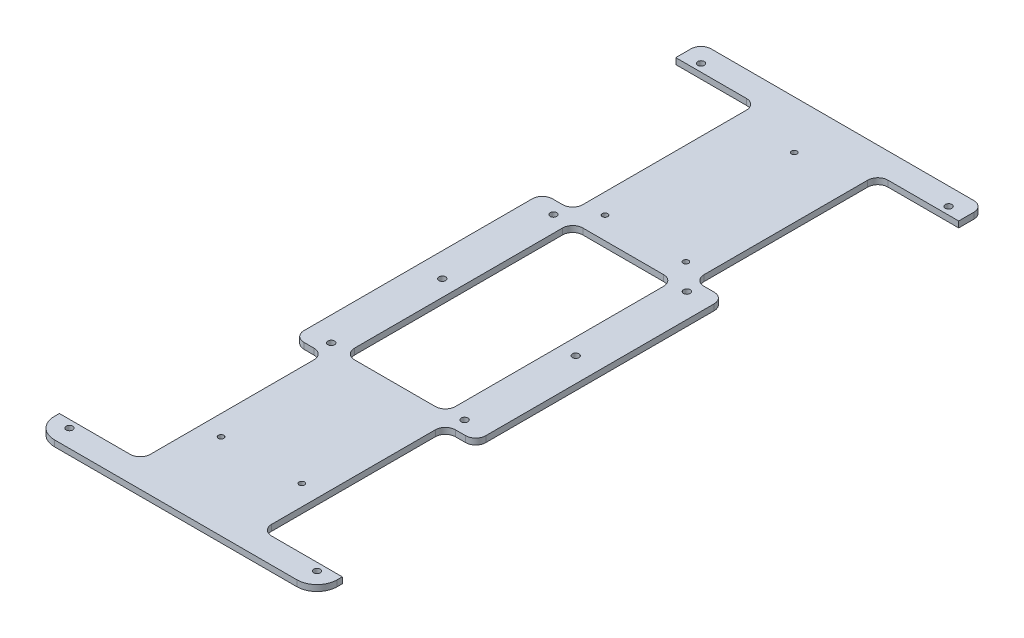
SolidWorks part; units mm, degrees
ref_plane "Front Plane" through (0, 0, 0) normal (0, 0, 1) x (1, 0, 0)
ref_plane "Top Plane" through (0, 0, 0) normal (0, 1, 0) x (1, 0, 0)
ref_plane "Right Plane" through (0, 0, 0) normal (1, 0, 0) x (0, 0, -1)
sketch "Sketch1" plane through (0, 0, 0) normal (0, 1, 0) x (1, 0, 0)
  line L0 (0, 0) -> (140, 0)
  line L1 (0, 0) -> (140, 0) construction
  line L2 (0, 0) -> (0, 330) construction
  line L3 (0, 330) -> (140, 330) construction
  line L4 (140, 0) -> (140, 330) construction
  line L5 (140, 0) -> (140, 12.5)
  line L6 (140, 12.5) -> (100, 12.5)
  line L7 (100, 12.5) -> (100, 103.5)
  line L11 (100, 226.5) -> (100, 317.5)
  line L12 (100, 317.5) -> (140, 317.5)
  line L13 (140, 317.5) -> (140, 330)
  line L14 (140, 330) -> (0, 330)
  line L15 (0, 330) -> (0, 317.5)
  line L16 (0, 317.5) -> (40, 317.5)
  line L17 (40, 317.5) -> (40, 226.5)
  line L21 (40, 103.5) -> (40, 12.5)
  line L22 (40, 12.5) -> (0, 12.5)
  line L23 (0, 12.5) -> (0, 0)
  line L24 (40, 226.5) -> (25, 226.5)
  line L25 (25, 226.5) -> (25, 103.5)
  line L26 (25, 103.5) -> (40, 103.5)
  line L27 (100, 226.5) -> (115, 226.5)
  line L28 (115, 226.5) -> (115, 103.5)
  line L29 (115, 103.5) -> (100, 103.5)
  dimension "D1" = 140
  dimension "D2" = 330
  dimension "D3" = 40
  dimension "D4" = 91
  dimension "D5" = 25
  dimension "D6" = 123
extrude "Boss-Extrude1" add sketch "Sketch1" along normal blind 3
fillet "Fillet1" radius 10 2 edges at (140, 1.5, 0) (0, 1.5, 0)
fillet "Fillet2" radius 5 6 edges at (0, 1.5, -330) (140, 1.5, -330) (115, 1.5, -226.5) (115, 1.5, -103.5) (25, 1.5, -103.5) (25, 1.5, -226.5)
sketch "Sketch2" plane through (0, 3, 0) normal (0, 1, 0) x (1, 0, 0)
  line L2 (37, 220) -> (37, 110) construction
  line L3 (25, 165) -> (37, 165) construction
  line L4 (25, 221.5) -> (25, 108.5) construction
  line L5 (70, 330) -> (70, 0) construction
  line L6 (135, 330) -> (5, 330) construction
  line L7 (10, 0) -> (130, 0) construction
  circle A0 centre (37, 220) radius 1.65
  circle A1 centre (37, 165) radius 1.65
  circle A2 centre (37, 110) radius 1.65
  circle A3 centre (103, 110) radius 1.65
  circle A4 centre (103, 165) radius 1.65
  circle A5 centre (103, 220) radius 1.65
  dimension "D3" = 3.3
  dimension "D1" = 12
  dimension "D2" = 110
extrude "Cut-Extrude1" cut sketch "Sketch2" against normal through all
sketch "Sketch3" plane through (0, 3, 0) normal (0, 1, 0) x (1, 0, 0)
  line L0 (0, 12.5) -> (8.75, 12.5) construction
  line L1 (40, 12.5) -> (0, 12.5) construction
  line L2 (8.75, 12.5) -> (8.75, 8.75) construction
  line L3 (70, 0) -> (70, 57.6288) construction
  line L4 (10, 0) -> (130, 0) construction
  circle A0 centre (8.75, 8.75) radius 1.65
  circle A1 centre (131.25, 8.75) radius 1.65
  dimension "D3" = 3.3
  dimension "D1" = 8.75
  dimension "D2" = 3.75
extrude "Cut-Extrude2" cut sketch "Sketch3" against normal through all
sketch "Sketch4" plane through (0, 3, 0) normal (0, 1, 0) x (1, 0, 0)
  line L0 (0, 317.5) -> (8.75, 317.5) construction
  line L1 (0, 317.5) -> (40, 317.5) construction
  line L2 (8.75, 317.5) -> (8.75, 321.25) construction
  line L3 (70, 330) -> (70, 288.2737) construction
  line L4 (135, 330) -> (5, 330) construction
  circle A0 centre (8.75, 321.25) radius 1.65
  circle A1 centre (131.25, 321.25) radius 1.65
  dimension "D3" = 3.3
  dimension "D1" = 8.75
  dimension "D2" = 3.75
extrude "Cut-Extrude3" cut sketch "Sketch4" against normal through all
fillet "Fillet3" radius 5 8 edges at (100, 1.5, -226.5) (40, 1.5, -226.5) (100, 1.5, -103.5) (40, 1.5, -103.5) (40, 1.5, -12.5) (100, 1.5, -12.5) (40, 1.5, -317.5) (100, 1.5, -317.5)
sketch "Sketch5" plane through (0, 3, 0) normal (0, 1, 0) x (1, 0, 0)
  line L0 (35, 12.5) -> (105, 12.5) construction
  line L1 (70, 12.5) -> (70, 42.5) construction
  line L2 (50, 42.5) -> (90, 42.5) construction
  line L3 (70, 42.5) -> (70, 232.5) construction
  line L4 (50, 232.5) -> (90, 232.5) construction
  line L5 (70, 330) -> (70, 306.15) construction
  line L6 (135, 330) -> (5, 330) construction
  circle A0 centre (50, 42.5) radius 1.35
  circle A1 centre (90, 42.5) radius 1.35
  circle A2 centre (50, 232.5) radius 1.35
  circle A3 centre (90, 232.5) radius 1.35
  circle A4 centre (70, 306.15) radius 1.35
  point P8 (70, 42.5)
  point P14 (70, 232.5)
  dimension "D3" = 2.7
  dimension "D1" = 30
  dimension "D2" = 40
  dimension "D4" = 190
  dimension "D5" = 40
  dimension "D6" = 23.85
extrude "Cut-Extrude4" cut sketch "Sketch5" against normal blind 10
sketch "Sketch6" plane through (0, 3, 0) normal (0, 1, 0) x (1, 0, 0)
  line L0 (35, 226.5) -> (105, 226.5) construction
  line L1 (45, 221.5) -> (95, 221.5)
  line L2 (45, 221.5) -> (45, 108.5)
  line L3 (45, 108.5) -> (95, 108.5)
  line L4 (95, 221.5) -> (95, 108.5)
  line L5 (35, 103.5) -> (105, 103.5) construction
  line L6 (70, 103.5) -> (70, 226.5) construction
  arc A0 (105, 103.5) -> (100, 98.5) centre (105, 98.5) ccw construction
  point P16 (70, 221.5)
  dimension "D1" = 5
  dimension "D2" = 5
  dimension "D3" = 50
extrude "Cut-Extrude5" cut sketch "Sketch6" against normal blind 10
fillet "Fillet4" radius 5 4 edges at (95, 1.5, -108.5) (45, 1.5, -108.5) (95, 1.5, -221.5) (45, 1.5, -221.5)
